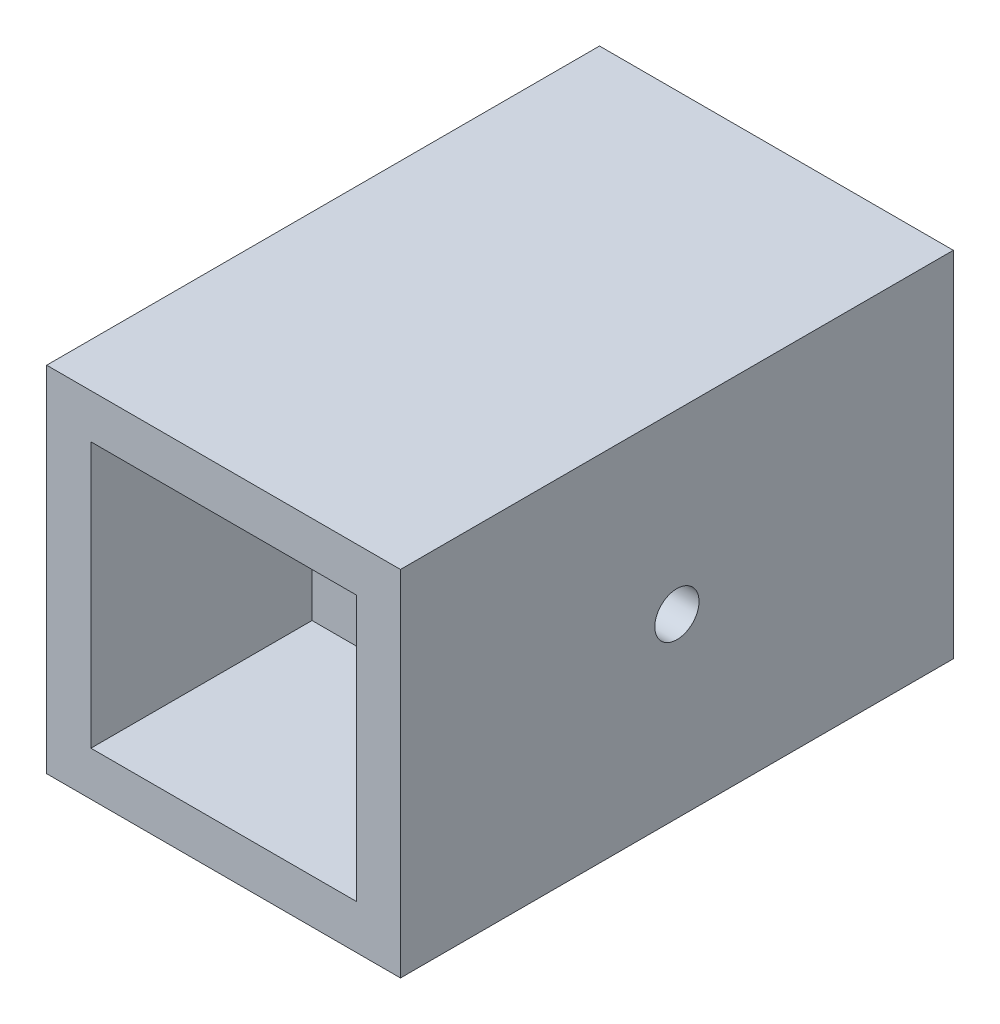
SolidWorks part; units mm, degrees
ref_plane "前视基准面" through (0, 0, 0) normal (0, 0, 1) x (1, 0, 0)
ref_plane "上视基准面" through (0, 0, 0) normal (0, 1, 0) x (1, 0, 0)
ref_plane "右视基准面" through (0, 0, 0) normal (1, 0, 0) x (0, 0, -1)
sketch "草图1" plane through (0, 0, 0) normal (0, 0, 1) x (1, 0, 0)
  line L1 (0, 0) -> (16, 0)
  line L2 (0, 0) -> (0, 16)
  line L3 (0, 16) -> (16, 16)
  line L4 (16, 0) -> (16, 16)
  point P5 (0, 0)
extrude "凸台-拉伸2" add sketch "草图1" along normal blind 25
sketch "草图2" plane through (0, 0, 0) normal (0, 0, -1) x (-1, 0, 0)
  line L1 (-2, 2) -> (-14, 2)
  line L2 (-2, 2) -> (-2, 14)
  line L3 (-2, 14) -> (-14, 14)
  line L4 (-14, 2) -> (-14, 14)
  point P0 (-2, 2)
  point P5 (0, 0)
  point P6 (0, 0)
extrude "切除-拉伸1" cut sketch "草图2" against normal blind 10
sketch "草图3" plane through (16, 0, 0) normal (1, 0, 0) x (0, 0, -1)
  circle A0 centre (-12.5, 7) radius 1
  point P0 (-12.5, 7)
sketch "草图4" plane through (0, 0, 25) normal (0, 0, 1) x (1, 0, 0)
  line L1 (2, 2) -> (14, 2)
  line L2 (2, 2) -> (2, 14)
  line L3 (2, 14) -> (14, 14)
  line L4 (14, 2) -> (14, 14)
  point P0 (2, 2)
  point P5 (0, 0)
  point P6 (0, 0)
extrude "切除-拉伸3" cut sketch "草图4" against normal blind 10
sketch "草图5" plane through (16, 0, 0) normal (1, 0, 0) x (0, 0, -1)
  circle A0 centre (-12.5, 8) radius 1
  point P0 (-12.5, 8)
  point P3 (0, 0)
extrude "切除-拉伸4" cut sketch "草图5" against normal blind 18
